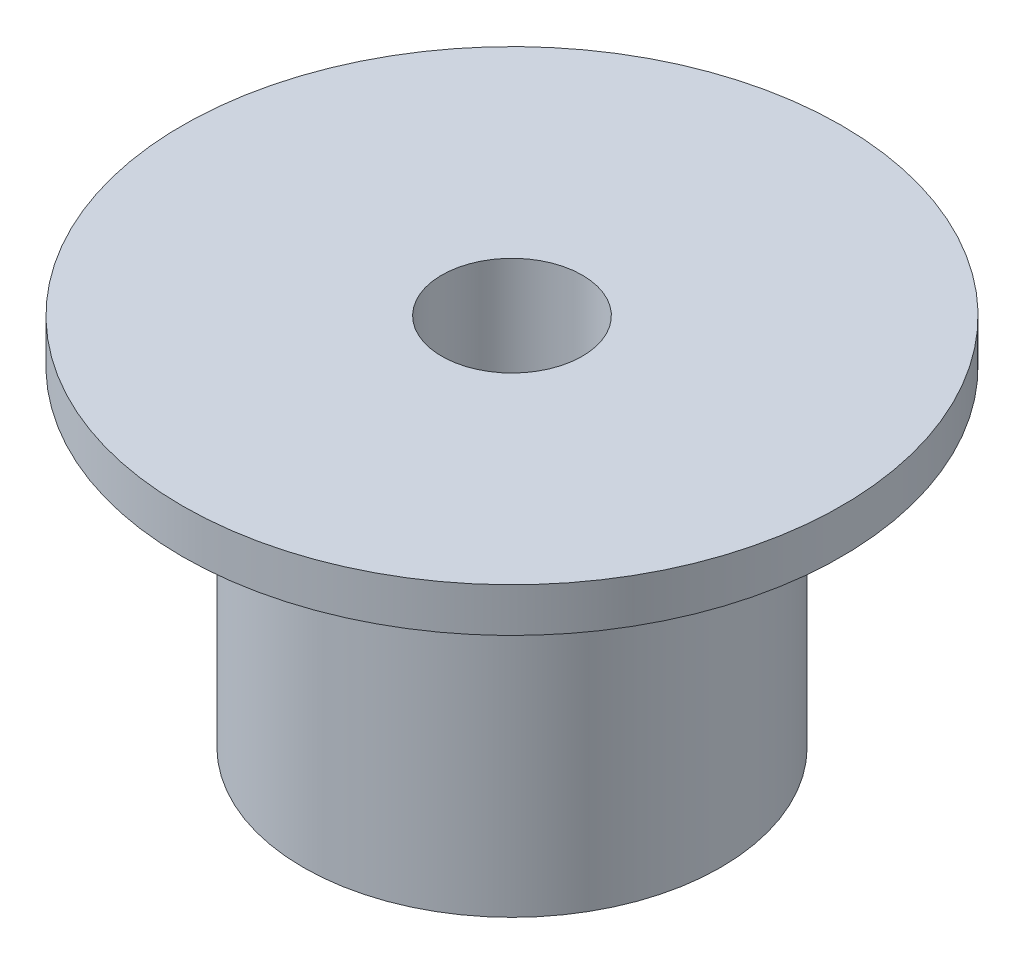
SolidWorks part; units mm, degrees
ref_plane "Front Plane" through (0, 0, 0) normal (0, 0, 1) x (1, 0, 0)
ref_plane "Top Plane" through (0, 0, 0) normal (0, 1, 0) x (1, 0, 0)
ref_plane "Right Plane" through (0, 0, 0) normal (1, 0, 0) x (0, 0, -1)
sketch "Sketch1" plane through (0, 0, 0) normal (0, 1, 0) x (1, 0, 0)
  circle A0 centre (0, 0) radius 1.6256
  circle A1 centre (0, 0) radius 4.826
  dimension "D1" = 3.2512
  dimension "D2" = 9.652
extrude "Boss-Extrude1" add sketch "Sketch1" along normal blind 7.62
sketch "Sketch2" plane through (0, 7.62, 0) normal (0, 1, 0) x (1, 0, 0)
  circle A0 centre (0, 0) radius 7.62
  dimension "D1" = 15.24
extrude "Boss-Extrude2" add sketch "Sketch2" along normal blind 1.016
sketch "Sketch3" plane through (0, 0, 0) normal (0, -1, 0) x (1, 0, 0)
  circle A0 centre (0, 0) radius 1.6256
extrude "Cut-Extrude1" cut sketch "Sketch3" against normal through all
